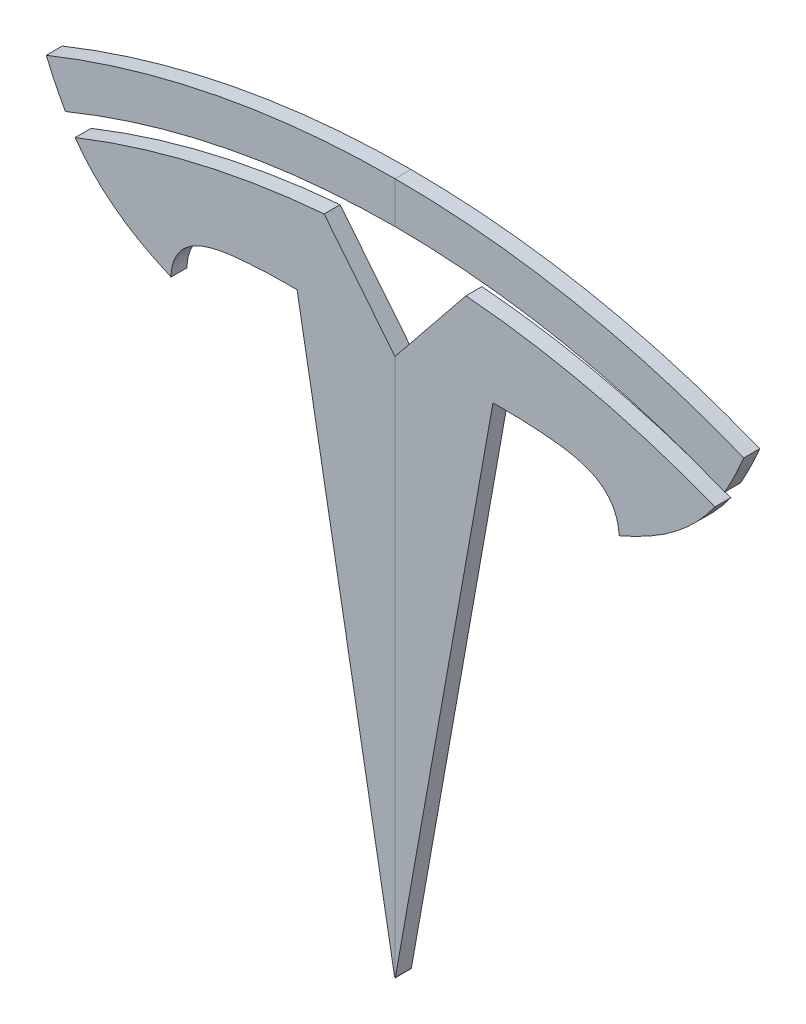
SolidWorks part; units mm, degrees
ref_plane "前视基准面" through (0, 0, 0) normal (0, 0, 1) x (1, 0, 0)
ref_plane "上视基准面" through (0, 0, 0) normal (0, 1, 0) x (1, 0, 0)
ref_plane "右视基准面" through (0, 0, 0) normal (1, 0, 0) x (0, 0, -1)
other "Configuration Table"
sketch "草图4" plane through (0, 0, 0) normal (0, 0, 1) x (1, 0, 0)
  line L0 (130.9079, 135.6961) -> (129.7541, 135.6919)
  line L2 (114.4764, 157.5044) -> (114.4404, 157.5344)
  line L4 (141.6228, 130.1692) -> (141.6782, 130.0404)
  line L5 (117.4955, 134.5893) -> (126.3676, 145.6067)
  line L6 (141.5654, 130.2797) -> (141.6228, 130.1692)
  line L7 (155.4, 130.8171) -> (155.0331, 130.5035)
  line L8 (138.8262, 135.1978) -> (138.2117, 135.2922)
  line L9 (117.4957, 157.5424) -> (117.4948, 63.5351)
  line L13 (163.2382, 141.2721) -> (163.2406, 141.2717)
  line L28 (141.3497, 130.5394) -> (141.0804, 130.7711)
  line L33 (139.0596, 131.4628) -> (138.3526, 131.6183)
  line L36 (132.7804, 132.0546) -> (121.1109, 66.6479)
  line L52 (117.4277, 134.6114) -> (117.4815, 134.5881)
  line L53 (117.4815, 134.5881) -> (117.5338, 134.6114)
  line L55 (129.7541, 135.6919) -> (117.5482, 67.34)
  line L56 (117.5482, 67.34) -> (117.4885, 67.2106)
  line L57 (117.4885, 67.2106) -> (117.4275, 67.34)
  arc A12 (117.4948, 63.5351) -> (121.1109, 66.6479) centre (117.4948, 67.1919) ccw
  arc A24 (141.9175, 129.0493) -> (147.561, 126.1632) centre (145.6073, 129.3037) ccw
  arc A25 (138.3526, 131.6183) -> (132.7799, 132.0522) centre (131.5125, 79.7666) ccw
  arc A26 (141.9257, 128.9506) -> (141.6782, 130.0404) centre (138.3086, 128.7022) ccw
  arc A27 (138.2117, 135.2922) -> (130.9079, 135.6961) centre (131.135, 73.5639) ccw
  arc A28 (141.5654, 130.2797) -> (141.3497, 130.5394) centre (140.6875, 129.7698) ccw
  arc A29 (145.5298, 129.1839) -> (144.1966, 132.782) centre (139.9685, 129.1694) ccw
  arc A30 (141.0804, 130.7711) -> (139.0596, 131.4628) centre (137.0302, 122.2365) ccw
  arc A31 (147.561, 126.1632) -> (155.0331, 130.5035) centre (134.7338, 156.8482) ccw
  arc A32 (155.4, 130.8171) -> (159.5362, 134.9472) centre (139.3739, 151.0037) ccw
  arc A33 (161.1462, 145.4194) -> (117.4956, 153.8609) centre (117.517, 36.8936) ccw
  arc A34 (162.4456, 148.7976) -> (117.4957, 157.5424) centre (117.4957, 37.644) ccw
  arc A35 (142.0271, 134.3247) -> (138.8262, 135.1978) centre (136.6969, 121.0871) ccw
  arc A39 (144.1966, 132.782) -> (141.3847, 134.5656) centre (139.4299, 128.3755) ccw
  arc A40 (114.4404, 157.5344) -> (114.4323, 157.5033) centre (139.3739, 151.0037) ccw
  arc A50 (163.2406, 141.2717) -> (163.2536, 141.3035) centre (139.3739, 151.0037) ccw
  arc A51 (159.5208, 134.9278) -> (164.4616, 143.9676) centre (118.6707, 163.1248) ccw
  arc A52 (164.4391, 143.9141) -> (162.3979, 148.8169) centre (161.0337, 145.3726) ccw
  arc A53 (158.7524, 140.5171) -> (117.4956, 148.6709) centre (117.4474, 39.9732) ccw
  arc A54 (158.7524, 140.5171) -> (161.1462, 145.4194) centre (118.704, 163.108) ccw
  arc A55 (157.532, 138.3053) -> (117.4956, 145.9707) centre (117.4917, 37.5618) ccw
  arc A56 (151.4254, 132.3243) -> (151.3907, 132.3362) centre (131.0857, 72.6914) ccw
  arc A58 (114.4764, 157.5044) -> (114.4323, 157.5033) centre (117.4957, 37.644) ccw
  arc A61 (151.3907, 132.3362) -> (157.532, 138.3053) centre (138.3895, 151.8563) ccw
  arc A62 (145.5298, 129.1839) -> (151.4254, 132.3243) centre (130.8597, 163.8289) ccw
extrude "凸台-拉伸1" add sketch "草图4" along normal blind 2
mirror "镜向1" about plane through (117.4943, -0.001, 2) normal (1, 0, 0) of bodies 194 195
